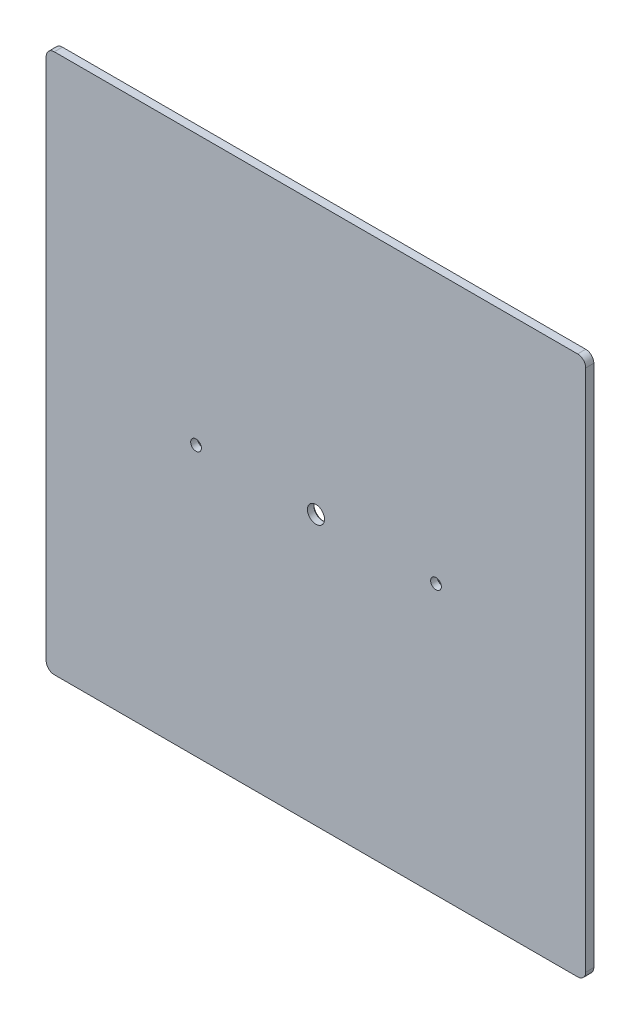
SolidWorks part; units mm, degrees
ref_plane "Front Plane" through (0, 0, 0) normal (0, 0, 1) x (1, 0, 0)
ref_plane "Top Plane" through (0, 0, 0) normal (0, 1, 0) x (1, 0, 0)
ref_plane "Right Plane" through (0, 0, 0) normal (1, 0, 0) x (0, 0, -1)
sketch "Baseplate" plane through (0, 0, 0) normal (0, 0, 1) x (1, 0, 0)
  line L2 (-100, 100) -> (100, 100)
  line L3 (-100, 100) -> (-100, -100)
  line L4 (-100, -100) -> (100, -100)
  line L5 (100, 100) -> (100, -100)
  line L6 (-100, 100) -> (100, -100) construction
  line L7 (-100, -100) -> (100, 100) construction
  point P2 (0, 0)
  dimension "D1" = 200
  dimension "D2" = 200
extrude "Boss-Extrude1" add sketch "Baseplate" along normal blind 3
sketch "LIDAR PLACEMENT" [suppressed] plane through (0, 0, 3) normal (0, 0, 1) x (1, 0, 0)
  circle A0 centre (0, 0) radius 51.65
  circle A1 centre (44.45, 0) radius 1.015
  dimension "D1" = 103.3
  dimension "2.03" = 2.03
  dimension "D2" = 44.45
fillet "Fillet1" radius 3 4 edges at (-100, -100, 1.5) (100, -100, 1.5) (100, 100, 1.5) (-100, 100, 1.5)
hole_wizard "1/4 Inch Bolt Hole" positions "Sketch7" profile "Sketch8" hole size "1/4" standard "ANSI Inch" end condition through all
sketch "Sketch7" plane through (0, 0, 0) normal (0, 0, -1) x (-1, 0, 0)
  point P0 (0, 0)
sketch "Sketch8" plane through (0, 0, 0) normal (1, 0, 0) x (0, 1, 0)
  line L0 (0, 0) -> (0, 3)
  line L1 (0, 3) -> (3.175, 3)
  line L2 (3.175, 3) -> (3.175, 0.635)
  line L3 (3.175, 0.635) -> (3.81, 0)
  line L5 (3.81, 0) -> (0, 0)
  line L6 (-3.175, 0.635) -> (-3.81, 0) construction
  line L11 (0, -6.35) -> (0, 107.95) construction
  dimension "Thru Hole Dia." = 6.35
  dimension "Thru Hole Depth" = 3
  dimension "Near C'Sink Dia." = 7.62
  dimension "Near C'Sink Angle" = 90
hole_wizard "5/32 Dowel Hole" positions "Sketch13" profile "Sketch14" hole size "5/32" standard "ANSI Inch" end condition through all
sketch "Sketch13" plane through (0, 0, 0) normal (0, 0, -1) x (-1, 0, 0)
  point P0 (-44.5, 0)
  point P2 (44.45, 0)
  dimension "D1" = 44.45
  dimension "D2" = 44.5
sketch "Sketch14" plane through (44.5, 0, 0) normal (1, 0, 0) x (0, 1, 0)
  line L0 (0, 0) -> (0, 3)
  line L1 (0, 3) -> (1.9844, 3)
  line L2 (1.9844, 3) -> (1.9844, 0.5328)
  line L3 (1.9844, 0.5328) -> (2.6194, 0)
  line L5 (2.6194, 0) -> (0, 0)
  line L6 (-1.9844, 0.5328) -> (-2.6194, 0) construction
  line L11 (0, -6.35) -> (0, 107.95) construction
  dimension "Thru Hole Dia." = 3.9688
  dimension "Thru Hole Depth" = 3
  dimension "Near C'Sink Dia." = 5.2387
  dimension "Near C'Sink Angle" = 100
